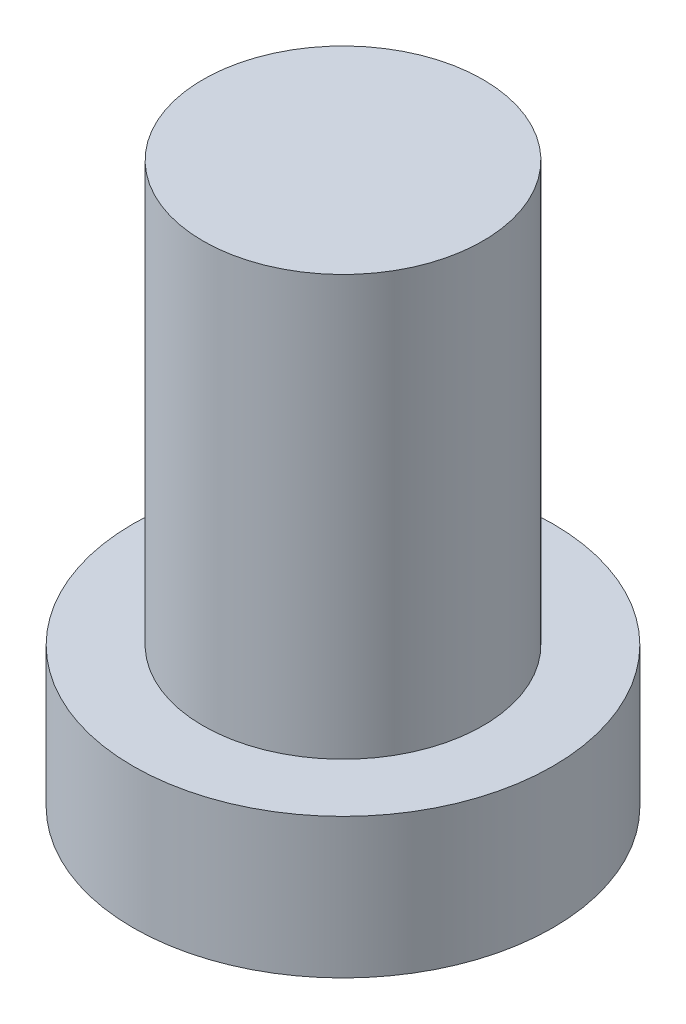
SolidWorks part; units mm, degrees
material "1023 Chapa de aço carbono (SS)"
ref_plane "Plano frontal" through (0, 0, 0) normal (0, 0, 1) x (1, 0, 0)
ref_plane "Plano superior" through (0, 0, 0) normal (0, 1, 0) x (1, 0, 0)
ref_plane "Plano direito" through (0, 0, 0) normal (1, 0, 0) x (0, 0, -1)
sketch "Esboço1" plane through (0, 0, 0) normal (0, 1, 0) x (1, 0, 0)
  circle A0 centre (0, 0) radius 15
  dimension "D1" = 30
extrude "Ressalto-extrusão1" add sketch "Esboço1" along normal blind 10
sketch "Esboço2" plane through (0, 10, 0) normal (0, 1, 0) x (1, 0, 0)
  circle A0 centre (0, 0) radius 10
  dimension "D1" = 20
extrude "Ressalto-extrusão2" add sketch "Esboço2" along normal blind 30
